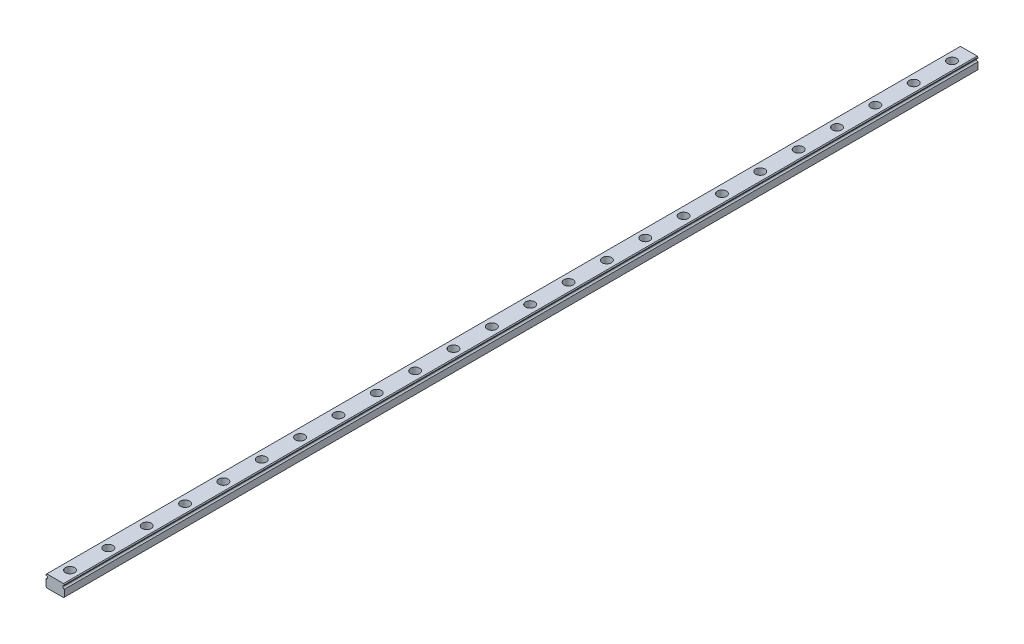
SolidWorks part; units mm, degrees
ref_plane "Front Plane" through (0, 0, 0) normal (0, 0, 1) x (1, 0, 0)
ref_plane "Top Plane" through (0, 0, 0) normal (0, 1, 0) x (1, 0, 0)
ref_plane "Right Plane" through (0, 0, 0) normal (1, 0, 0) x (0, 0, -1)
sketch "Sketch1" plane through (0, 0, 0) normal (0, 0, 1) x (1, 0, 0)
  line L0 (-5.5, 4) -> (-6, 3.5)
  line L1 (5.5, 4) -> (-5.5, 4)
  line L2 (6, 3.5) -> (6, -3.5)
  line L3 (5.5, -4) -> (-5.5, -4)
  line L4 (-6, 3.5) -> (-6, -3.5)
  line L5 (6, 4) -> (-6, -4) construction
  line L6 (6, -4) -> (-6, 4) construction
  line L7 (-5.5, -4) -> (-6, -3.5)
  line L8 (6, -3.5) -> (5.5, -4)
  line L9 (6, 3.5) -> (5.5, 4)
  line L10 (0, 0) -> (0, 7.4717)
  arc A0 (-6, 3) -> (-6, 1) centre (-6, 2) cw
  arc A1 (6, 3) -> (6, 1) centre (6, 2) ccw
  point P0 (0, 0)
  dimension "D4" = 1
  dimension "D1" = 12
  dimension "D2" = 8
  dimension "D3" = 2
extrude "Boss-Extrude1" add sketch "Sketch1" along normal blind 598
hole_wizard "CBORE for M5 Hex Head Bolt1" positions "Sketch2" profile "Sketch3" counterbore size "M5" standard "ANSI Metric" end condition through all
sketch "Sketch2" plane through (0, 4, 0) normal (0, 1, 0) x (1, 0, 0)
  line L0 (5.5, 0) -> (-5.5, 0) construction
  point P0 (0, -11)
  dimension "D1" = 11
sketch "Sketch3" plane through (0, 4, 11) normal (1, 0, 0) x (0, 0, 1)
  line L0 (0, 0) -> (0, 8)
  line L1 (0, 8) -> (1.75, 8)
  line L3 (1.75, 8) -> (1.75, 4.5)
  line L4 (1.75, 4.5) -> (3, 4.5)
  line L5 (3, 4.5) -> (3, 0)
  line L7 (3, 0) -> (0, 0)
  line L11 (0, -6.35) -> (0, 107.95) construction
  dimension "Thru Hole Dia." = 3.5
  dimension "Thru Hole Depth" = 8
  dimension "C'Bore Dia." = 6
  dimension "C'Bore Depth" = 4.5
pattern_linear "LPattern1" count 24 spacing 25.1 along (0, 0, 1) of "CBORE for M5 Hex Head Bolt1"
